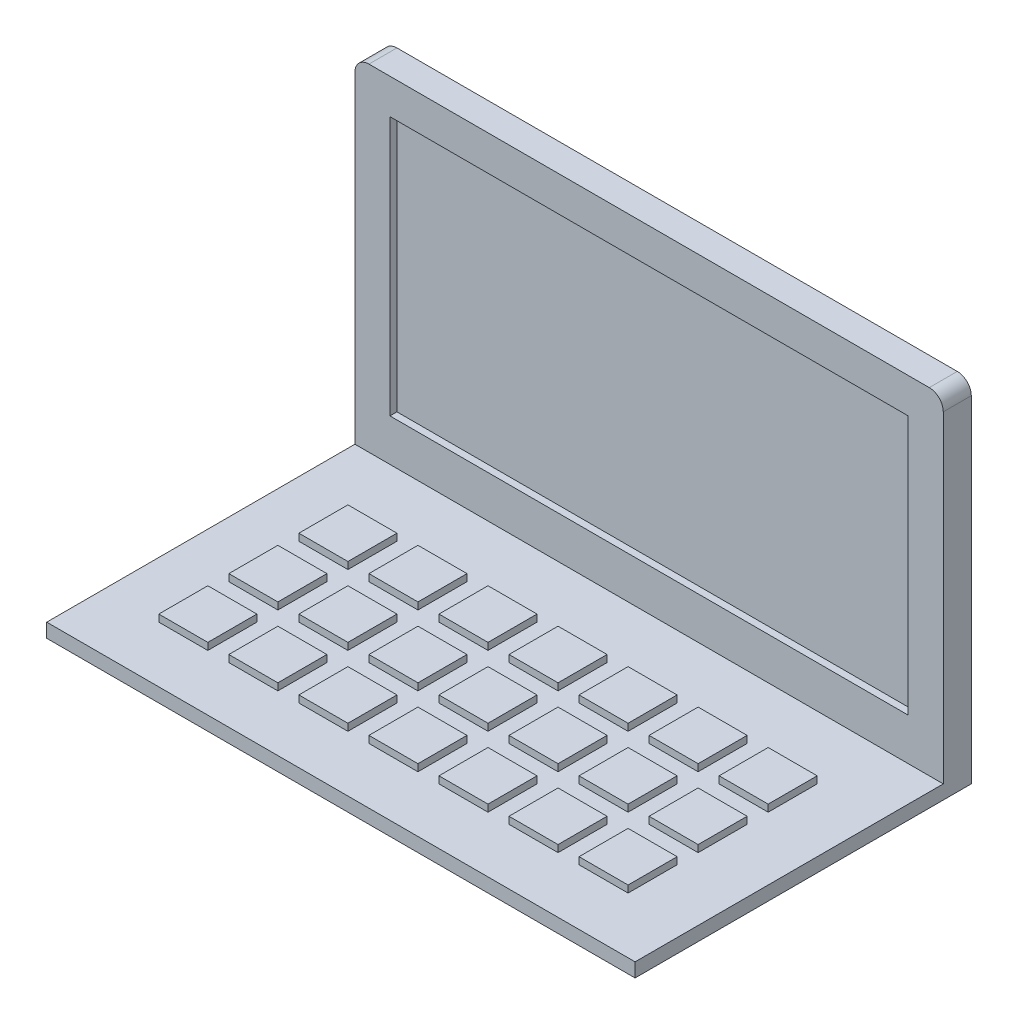
SolidWorks part; units mm, degrees
ref_plane "Front Plane" through (0, 0, 0) normal (0, 0, 1) x (1, 0, 0)
ref_plane "Top Plane" through (0, 0, 0) normal (0, 1, 0) x (1, 0, 0)
ref_plane "Right Plane" through (0, 0, 0) normal (1, 0, 0) x (0, 0, -1)
sketch "Sketch1" plane through (0, 0, 0) normal (0, 0, 1) x (1, 0, 0)
  line L0 (0, 0) -> (0, 2.5)
  line L1 (0, 2.5) -> (4.2, 2.5)
  line L2 (4.2, 2.5) -> (4.2, 0)
  line L3 (4.2, 0) -> (0, 0)
  dimension "D1" = 2.5
  dimension "D2" = 4.2
extrude "Boss-Extrude1" add sketch "Sketch1" along normal blind 0.2
sketch "Sketch2" plane through (0, 0, 0.2) normal (0, 0, 1) x (1, 0, 0)
  line L0 (0.25, 2.25) -> (0.25, 0.4)
  line L1 (0.25, 0.4) -> (3.95, 0.4)
  line L2 (3.95, 0.4) -> (3.95, 2.25)
  line L3 (3.95, 2.25) -> (0.25, 2.25)
  line L4 (0, 2.5) -> (0, 0) construction
  line L5 (0, 0) -> (4.2, 0) construction
  dimension "D1" = 3.7
  dimension "D2" = 0.25
  dimension "D3" = 1.85
  dimension "D4" = 0.4
extrude "Cut-Extrude1" cut sketch "Sketch2" against normal blind 0.05
sketch "Sketch3" plane through (0, 0, 0) normal (-1, 0, 0) x (0, 0, 1)
  line L0 (0, 0) -> (2.4, 0)
  line L1 (2.4, 0) -> (2.4, 0.1)
  line L2 (2.4, 0.1) -> (0, 0.1)
  line L3 (0, 2.5) -> (0, 0) construction
  line L4 (0, 0.1) -> (0, 0)
  dimension "D1" = 2.4
  dimension "D2" = 0.1
extrude "Boss-Extrude3" add sketch "Sketch3" against normal blind 4.2
fillet "Fillet3" radius 0.1 2 edges at (0, 2.5, 0.1) (4.2, 2.5, 0.1)
sketch "Sketch4" plane through (0, 0.1, 0) normal (0, 1, 0) x (1, 0, 0)
  line L0 (0.4, -1.65) -> (0.4, -2)
  line L1 (0.4, -2) -> (0.75, -2)
  line L2 (0.4, -1.65) -> (0.75, -1.65)
  line L3 (0.75, -1.65) -> (0.75, -2)
  line L4 (0, -2.4) -> (0, -0.2) construction
  line L5 (4.2, -2.4) -> (0, -2.4) construction
  line L6 (1.25, -1.65) -> (1.25, -2)
  line L7 (0.9, -2) -> (1.25, -2)
  line L8 (0.9, -1.65) -> (0.9, -2)
  line L9 (0.9, -1.65) -> (1.25, -1.65)
  line L10 (1.75, -1.65) -> (1.75, -2)
  line L11 (1.4, -2) -> (1.75, -2)
  line L12 (1.4, -1.65) -> (1.4, -2)
  line L13 (1.4, -1.65) -> (1.75, -1.65)
  line L14 (2.25, -1.65) -> (2.25, -2)
  line L15 (1.9, -2) -> (2.25, -2)
  line L16 (1.9, -1.65) -> (1.9, -2)
  line L17 (1.9, -1.65) -> (2.25, -1.65)
  line L18 (2.75, -1.65) -> (2.75, -2)
  line L19 (2.4, -2) -> (2.75, -2)
  line L20 (2.4, -1.65) -> (2.4, -2)
  line L21 (2.4, -1.65) -> (2.75, -1.65)
  line L22 (3.25, -1.65) -> (3.25, -2)
  line L23 (2.9, -2) -> (3.25, -2)
  line L24 (2.9, -1.65) -> (2.9, -2)
  line L25 (2.9, -1.65) -> (3.25, -1.65)
  line L26 (3.75, -1.65) -> (3.75, -2)
  line L27 (3.4, -2) -> (3.75, -2)
  line L28 (3.4, -1.65) -> (3.4, -2)
  line L29 (3.4, -1.65) -> (3.75, -1.65)
  line L30 (1.25, -1.15) -> (1.25, -1.5)
  line L31 (0.9, -1.5) -> (1.25, -1.5)
  line L32 (0.9, -1.15) -> (0.9, -1.5)
  line L33 (0.9, -1.15) -> (1.25, -1.15)
  line L34 (1.75, -1.15) -> (1.75, -1.5)
  line L35 (1.4, -1.5) -> (1.75, -1.5)
  line L36 (1.4, -1.15) -> (1.4, -1.5)
  line L37 (1.4, -1.15) -> (1.75, -1.15)
  line L38 (2.25, -1.15) -> (2.25, -1.5)
  line L39 (1.9, -1.5) -> (2.25, -1.5)
  line L40 (1.9, -1.15) -> (1.9, -1.5)
  line L41 (1.9, -1.15) -> (2.25, -1.15)
  line L42 (2.75, -1.15) -> (2.75, -1.5)
  line L43 (2.4, -1.5) -> (2.75, -1.5)
  line L44 (2.4, -1.15) -> (2.4, -1.5)
  line L45 (2.4, -1.15) -> (2.75, -1.15)
  line L46 (3.25, -1.15) -> (3.25, -1.5)
  line L47 (2.9, -1.5) -> (3.25, -1.5)
  line L48 (2.9, -1.15) -> (2.9, -1.5)
  line L49 (2.9, -1.15) -> (3.25, -1.15)
  line L50 (3.75, -1.15) -> (3.75, -1.5)
  line L51 (3.4, -1.5) -> (3.75, -1.5)
  line L52 (3.4, -1.15) -> (3.4, -1.5)
  line L53 (3.4, -1.15) -> (3.75, -1.15)
  line L54 (1.25, -0.65) -> (1.25, -1)
  line L55 (0.9, -1) -> (1.25, -1)
  line L56 (0.9, -0.65) -> (0.9, -1)
  line L57 (0.9, -0.65) -> (1.25, -0.65)
  line L58 (1.75, -0.65) -> (1.75, -1)
  line L59 (1.4, -1) -> (1.75, -1)
  line L60 (1.4, -0.65) -> (1.4, -1)
  line L61 (1.4, -0.65) -> (1.75, -0.65)
  line L62 (2.25, -0.65) -> (2.25, -1)
  line L63 (1.9, -1) -> (2.25, -1)
  line L64 (1.9, -0.65) -> (1.9, -1)
  line L65 (1.9, -0.65) -> (2.25, -0.65)
  line L66 (2.75, -0.65) -> (2.75, -1)
  line L67 (2.4, -1) -> (2.75, -1)
  line L68 (2.4, -0.65) -> (2.4, -1)
  line L69 (2.4, -0.65) -> (2.75, -0.65)
  line L70 (3.25, -0.65) -> (3.25, -1)
  line L71 (2.9, -1) -> (3.25, -1)
  line L72 (2.9, -0.65) -> (2.9, -1)
  line L73 (2.9, -0.65) -> (3.25, -0.65)
  line L74 (3.75, -0.65) -> (3.75, -1)
  line L75 (3.4, -1) -> (3.75, -1)
  line L76 (3.4, -0.65) -> (3.4, -1)
  line L77 (3.4, -0.65) -> (3.75, -0.65)
  line L78 (0.75, -1.15) -> (0.75, -1.5)
  line L79 (0.4, -1.5) -> (0.75, -1.5)
  line L80 (0.4, -1.15) -> (0.4, -1.5)
  line L81 (0.4, -1.15) -> (0.75, -1.15)
  line L82 (0.75, -0.65) -> (0.75, -1)
  line L83 (0.4, -1) -> (0.75, -1)
  line L84 (0.4, -0.65) -> (0.4, -1)
  line L85 (0.4, -0.65) -> (0.75, -0.65)
  line L86 (0.75, -1.65) -> (1.25, -1.65) construction
  dimension "D1" = 0.4
  dimension "D2" = 0.4
  dimension "D3" = 0.35
  dimension "D4" = 0.35
  dimension "D7" = 0.5
  dimension "D5" = 7
  dimension "D6" = 3
extrude "Boss-Extrude4" add sketch "Sketch4" along normal blind 0.05
